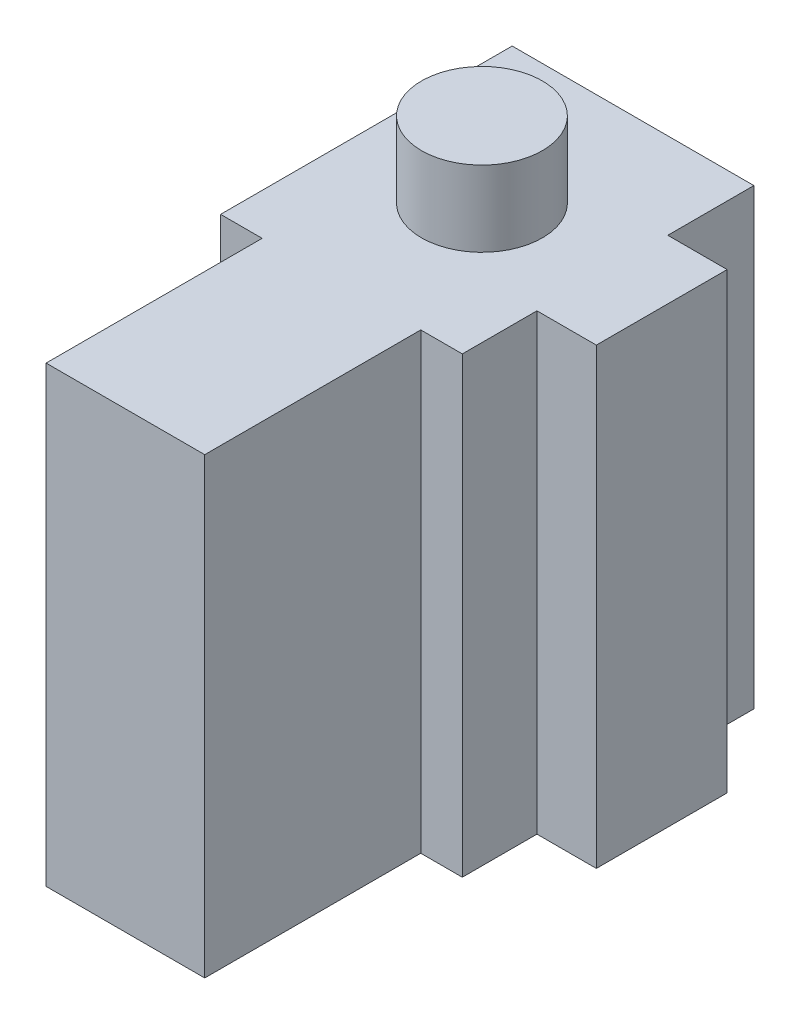
SolidWorks part; units mm, degrees
material "ABS"
ref_plane "Front Plane" through (0, 0, 0) normal (0, 0, 1) x (1, 0, 0)
ref_plane "Top Plane" through (0, 0, 0) normal (0, 1, 0) x (1, 0, 0)
ref_plane "Right Plane" through (0, 0, 0) normal (1, 0, 0) x (0, 0, -1)
sketch "Sketch1" plane through (0, 0, 0) normal (0, 1, 0) x (1, 0, 0)
  line L0 (0, 0) -> (0, 1.681)
  line L1 (0, 1.681) -> (-0.6985, 1.681)
  line L2 (-0.6985, 1.681) -> (-0.6985, 6.5832)
  line L3 (-0.6985, 6.5832) -> (3.3655, 6.5832)
  line L4 (3.3655, 6.5832) -> (3.3655, 5.1354)
  line L5 (3.3655, 5.1354) -> (4.3637, 5.1354)
  line L6 (4.3637, 5.1354) -> (4.3637, 2.9358)
  line L7 (4.3637, 2.9358) -> (3.3655, 2.9358)
  line L8 (3.3655, 2.9358) -> (3.3655, 1.681)
  line L9 (3.3655, 1.681) -> (2.667, 1.681)
  line L10 (2.667, 1.681) -> (2.667, -1.9512)
  line L11 (2.667, -1.9512) -> (0, -1.9512)
  line L12 (0, -1.9512) -> (0, 1.681)
  dimension "D2" = 4.064
  dimension "D3" = 1.4478
  dimension "D4" = 0.9982
  dimension "D5" = 2.1996
  dimension "D6" = 1.2548
  dimension "D7" = 0.6985
  dimension "D9" = 0.6985
  dimension "D8" = 3.6322
extrude "Boss-Extrude1" add sketch "Sketch1" along normal blind 7.62 contours L12 L11 L10 L9 L8 L7 L6 L5 L4 L3 L2 L1 L0
sketch "Sketch2" plane through (0, 7.62, 0) normal (0, 1, 0) x (1, 0, 0)
  line L0 (0.8255, 4.0432) -> (1.3335, 4.0432) construction
  line L2 (1.3335, 6.5832) -> (1.3335, 2.4589) construction
  line L3 (-0.6985, 6.5832) -> (3.3655, 6.5832) construction
  circle A1 centre (1.3335, 4.0432) radius 1.016
  dimension "D1" = 2.032
  dimension "D2" = 0.508
  dimension "D4" = 2.54
extrude "Boss-Extrude2" add sketch "Sketch2" along normal blind 1.27 contours A1
equation "\"D8@Sketch1\"=.143"
